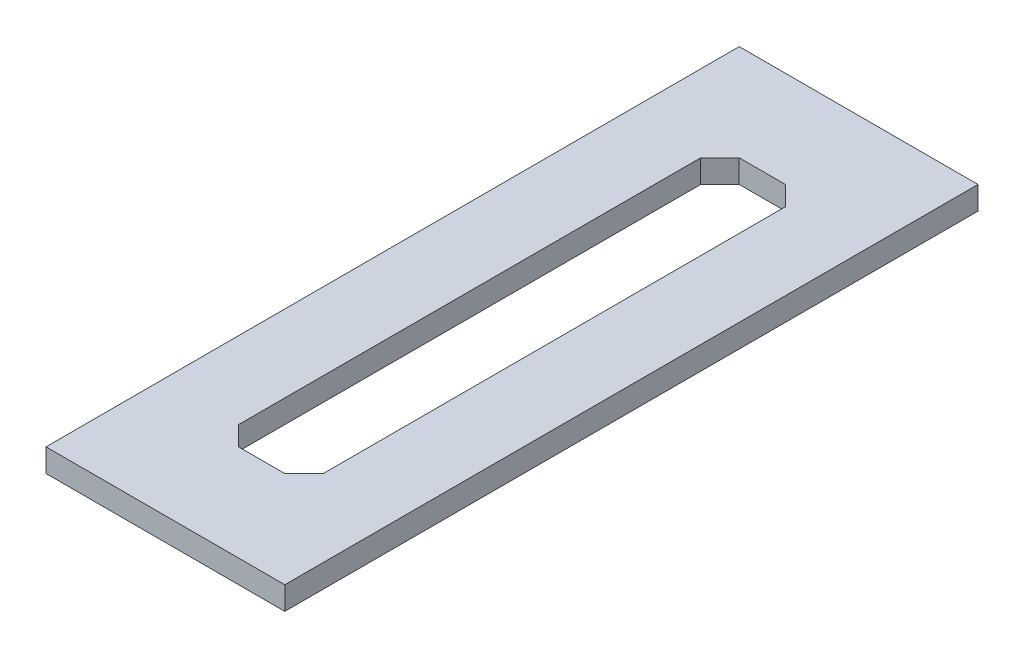
SolidWorks part; units mm, degrees
ref_plane "Front Plane" through (0, 0, 0) normal (0, 0, 1) x (1, 0, 0)
ref_plane "Top Plane" through (0, 0, 0) normal (0, 1, 0) x (1, 0, 0)
ref_plane "Right Plane" through (0, 0, 0) normal (1, 0, 0) x (0, 0, -1)
sketch "Sketch1" plane through (0, 0, 0) normal (0, 1, 0) x (1, 0, 0)
  line L0 (-48.3504, 84.7954) -> (-43.3504, 79.7954)
  line L1 (-85.3504, -70.2046) -> (-23.3504, -70.2046)
  line L2 (-85.3504, -70.2046) -> (-85.3504, 109.7954)
  line L3 (-85.3504, 109.7954) -> (-23.3504, 109.7954)
  line L4 (-23.3504, -70.2046) -> (-23.3504, 109.7954)
  line L5 (-60.3504, -45.2046) -> (-48.3504, -45.2046)
  line L6 (-65.3504, -40.2046) -> (-65.3504, 79.7954)
  line L7 (-60.3504, 84.7954) -> (-48.3504, 84.7954)
  line L8 (-43.3504, -40.2046) -> (-43.3504, 79.7954)
  line L9 (-65.3504, 79.7954) -> (-60.3504, 84.7954)
  line L10 (-60.3504, -45.2046) -> (-65.3504, -40.2046)
  line L11 (-48.3504, -45.2046) -> (-43.3504, -40.2046)
  point P4 (-65.3504, -45.2046)
  point P5 (-43.3504, 84.7954)
  point P6 (-65.3504, 84.7954)
  point P7 (-43.3504, -45.2046)
  dimension "D1" = 180
  dimension "D2" = 62
  dimension "D3" = 25
  dimension "D4" = 25
  dimension "D5" = 20
  dimension "D6" = 20
extrude "Boss-Extrude1" add sketch "Sketch1" along normal blind 6
